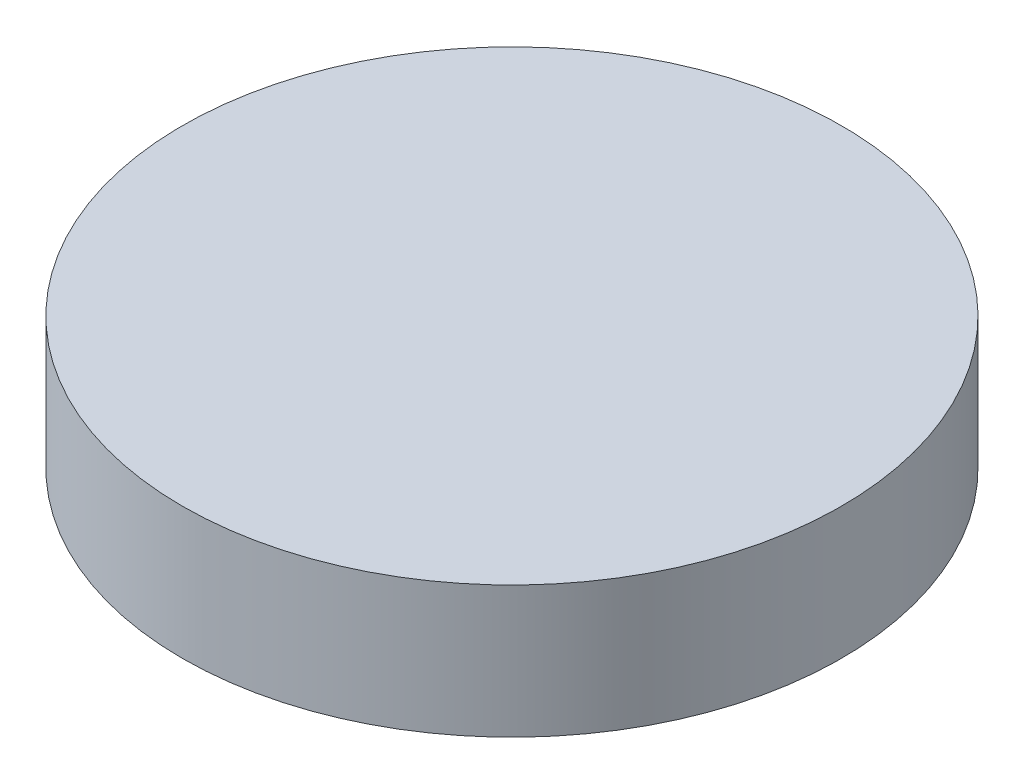
SolidWorks part; units mm, degrees
ref_plane "Front Plane" through (0, 0, 0) normal (0, 0, 1) x (1, 0, 0)
ref_plane "Top Plane" through (0, 0, 0) normal (0, 1, 0) x (1, 0, 0)
ref_plane "Right Plane" through (0, 0, 0) normal (1, 0, 0) x (0, 0, -1)
sketch "Sketch1" plane through (0, 0, 0) normal (0, 1, 0) x (1, 0, 0)
  circle A0 centre (0, 0) radius 10
extrude "Boss-Extrude1" add sketch "Sketch1" along normal blind 4
